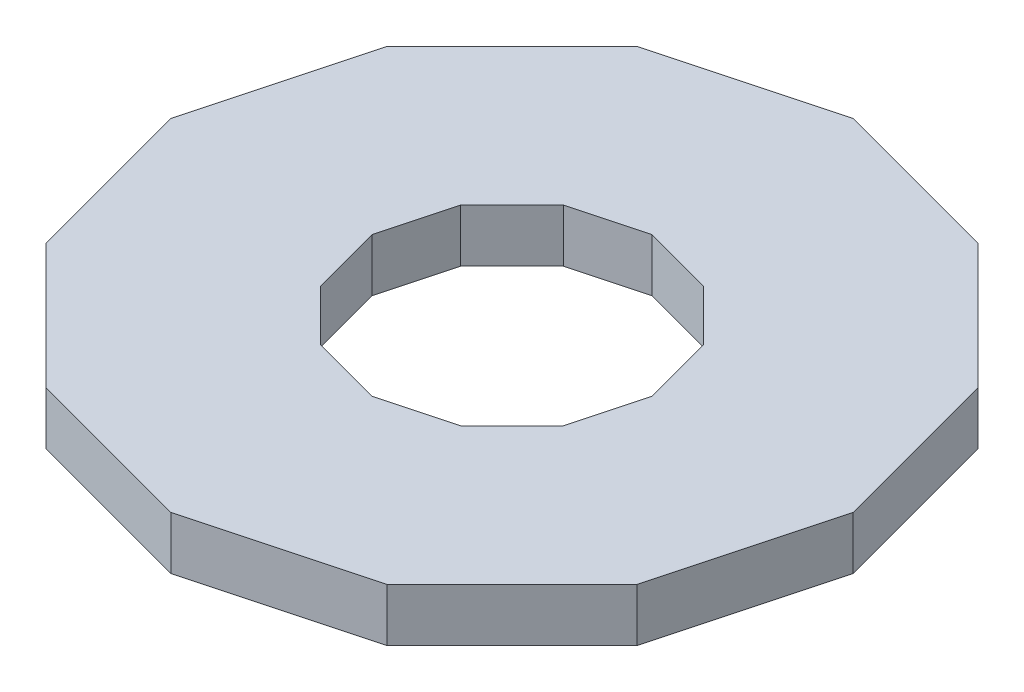
SolidWorks part; units mm, degrees
ref_plane "Front Plane" through (0, 0, 0) normal (0, 0, 1) x (1, 0, 0)
ref_plane "Top Plane" through (0, 0, 0) normal (0, 1, 0) x (1, 0, 0)
ref_plane "Right Plane" through (0, 0, 0) normal (1, 0, 0) x (0, 0, -1)
sketch "Sketch2" plane through (0, 0, 0) normal (0, 1, 0) x (1, 0, 0)
  line L0 (0, 0) -> (-50.3585, 0) construction
  line L1 (-122.6726, 0) -> (-106.2376, -61.3363)
  line L2 (-106.2376, -61.3363) -> (-61.3363, -106.2376)
  line L3 (-61.3363, -106.2376) -> (0, -122.6726)
  line L4 (0, -122.6726) -> (61.3363, -106.2376)
  line L5 (61.3363, -106.2376) -> (106.2376, -61.3363)
  line L6 (106.2376, -61.3363) -> (122.6726, 0)
  line L7 (122.6726, 0) -> (106.2376, 61.3363)
  line L8 (106.2376, 61.3363) -> (61.3363, 106.2376)
  line L9 (61.3363, 106.2376) -> (0, 122.6726)
  line L10 (0, 122.6726) -> (-61.3363, 106.2376)
  line L11 (-61.3363, 106.2376) -> (-106.2376, 61.3363)
  line L12 (-106.2376, 61.3363) -> (-122.6726, 0)
  line L13 (-50.3585, 0) -> (-43.6118, -25.1793)
  line L14 (-43.6118, -25.1793) -> (-25.1793, -43.6118)
  line L15 (-25.1793, -43.6118) -> (0, -50.3585)
  line L16 (0, -50.3585) -> (25.1793, -43.6118)
  line L17 (25.1793, -43.6118) -> (43.6118, -25.1793)
  line L18 (43.6118, -25.1793) -> (50.3585, 0)
  line L19 (50.3585, 0) -> (43.6118, 25.1793)
  line L20 (43.6118, 25.1793) -> (25.1793, 43.6118)
  line L21 (25.1793, 43.6118) -> (0, 50.3585)
  line L22 (0, 50.3585) -> (-25.1793, 43.6118)
  line L23 (-25.1793, 43.6118) -> (-43.6118, 25.1793)
  line L24 (-43.6118, 25.1793) -> (-50.3585, 0)
  line L25 (-122.6726, 0) -> (-50.3585, 0) construction
  circle A0 centre (0, 0) radius 118.4926 construction
  circle A1 centre (0, 0) radius 48.6426 construction
  dimension "D1" = 63.5
  dimension "D2" = 69.85
extrude "Boss-Extrude2" add sketch "Sketch2" along normal blind 19.05
